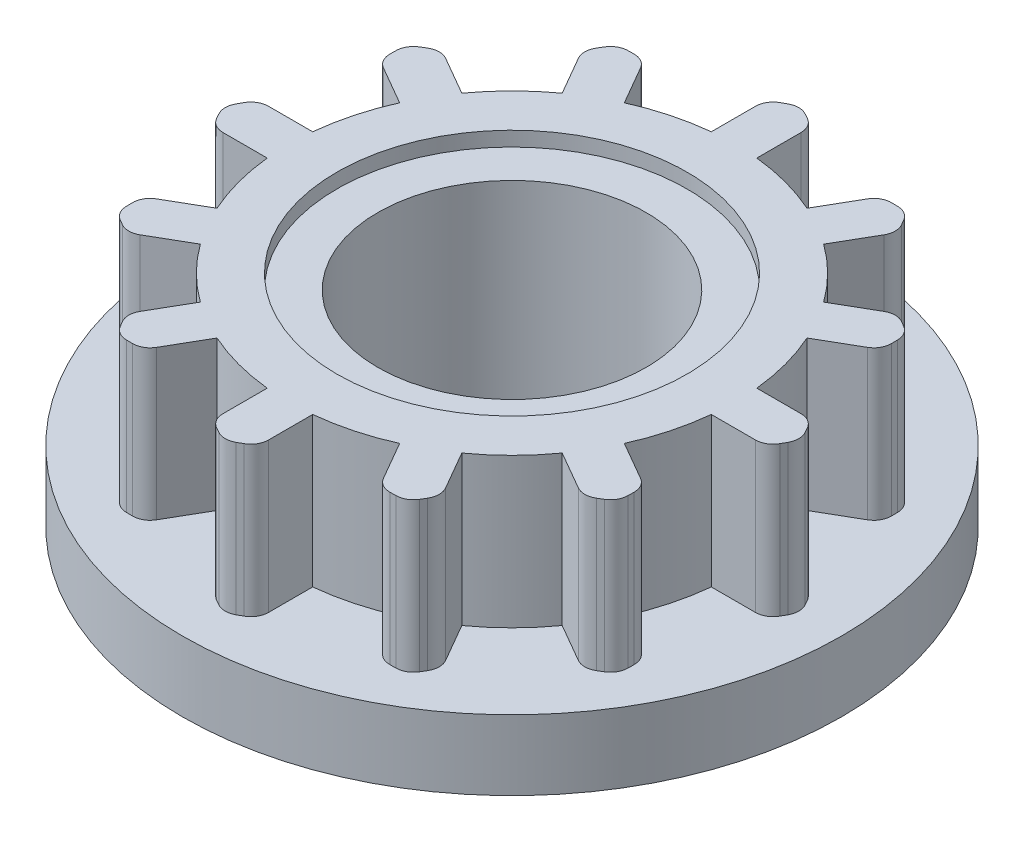
SolidWorks part; units mm, degrees
ref_plane "Front Plane" through (0, 0, 0) normal (0, 0, 1) x (1, 0, 0)
ref_plane "Top Plane" through (0, 0, 0) normal (0, 1, 0) x (1, 0, 0)
ref_plane "Right Plane" through (0, 0, 0) normal (1, 0, 0) x (0, 0, -1)
sketch "Sketch2" plane through (0, 0, 0) normal (0, 1, 0) x (1, 0, 0)
  circle A0 centre (0, 0) radius 5.65
  dimension "D1" = 11.3
extrude "Boss-Extrude1" add sketch "Sketch2" along normal blind 1.2
sketch "Sketch3" plane through (0, 1.2, 0) normal (0, 1, 0) x (1, 0, 0)
  circle A0 centre (0, 0) radius 3.825
  dimension "D1" = 7.65
extrude "Boss-Extrude2" add sketch "Sketch3" along normal blind 2.56
sketch "Sketch5" plane through (0, 0, 0) normal (0, -1, 0) x (1, 0, 0)
  circle A0 centre (0, 0) radius 3.9
  dimension "D1" = 7.8
extrude "Boss-Extrude4" add sketch "Sketch5" along normal blind 0.9
sketch "Sketch9" plane through (0, 1.2, 0) normal (0, 1, 0) x (1, 0, 0)
  line L1 (0.39, 2.91) -> (-0.39, 2.91)
  line L2 (0.39, 2.91) -> (0.39, 4.74)
  line L4 (-0.39, 2.91) -> (-0.39, 4.74)
  line L5 (0.39, 2.91) -> (-0.39, 4.74) construction
  line L6 (0.39, 4.74) -> (-0.39, 2.91) construction
  line L7 (-0.39, 4.74) -> (0, 4.957)
  line L8 (0, 4.957) -> (0.39, 4.74)
  point P0 (0, 4.4125)
  dimension "D1" = 1.83
  dimension "D2" = 0.78
  dimension "D3" = 4.4125
extrude "Boss-Extrude5" add sketch "Sketch9" along normal blind 2.56
fillet "Fillet12" radius 0.3 3 edges at (0, 2.48, -4.957) (0.39, 2.48, -4.74) (-0.39, 2.48, -4.74)
pattern_circular "CirPattern3" count 12 over 360 about axis through (0, 0, 0) along (0, 1, 0) of "Boss-Extrude5", "Fillet12"
sketch "Sketch10" plane through (0, 3.76, 0) normal (0, 1, 0) x (1, 0, 0)
  circle A0 centre (0, 0) radius 3
  circle A1 centre (0, 0) radius 2.3
  dimension "D1" = 6
  dimension "D2" = 4.6
extrude "Cut-Extrude3" cut sketch "Sketch10" against normal through all contours A1
sketch "Sketch11" plane through (0, 3.76, 0) normal (0, 1, 0) x (1, 0, 0)
  circle A0 centre (0, 0) radius 3
  dimension "D1" = 6
extrude "Cut-Extrude4" cut sketch "Sketch11" against normal blind 0.25
